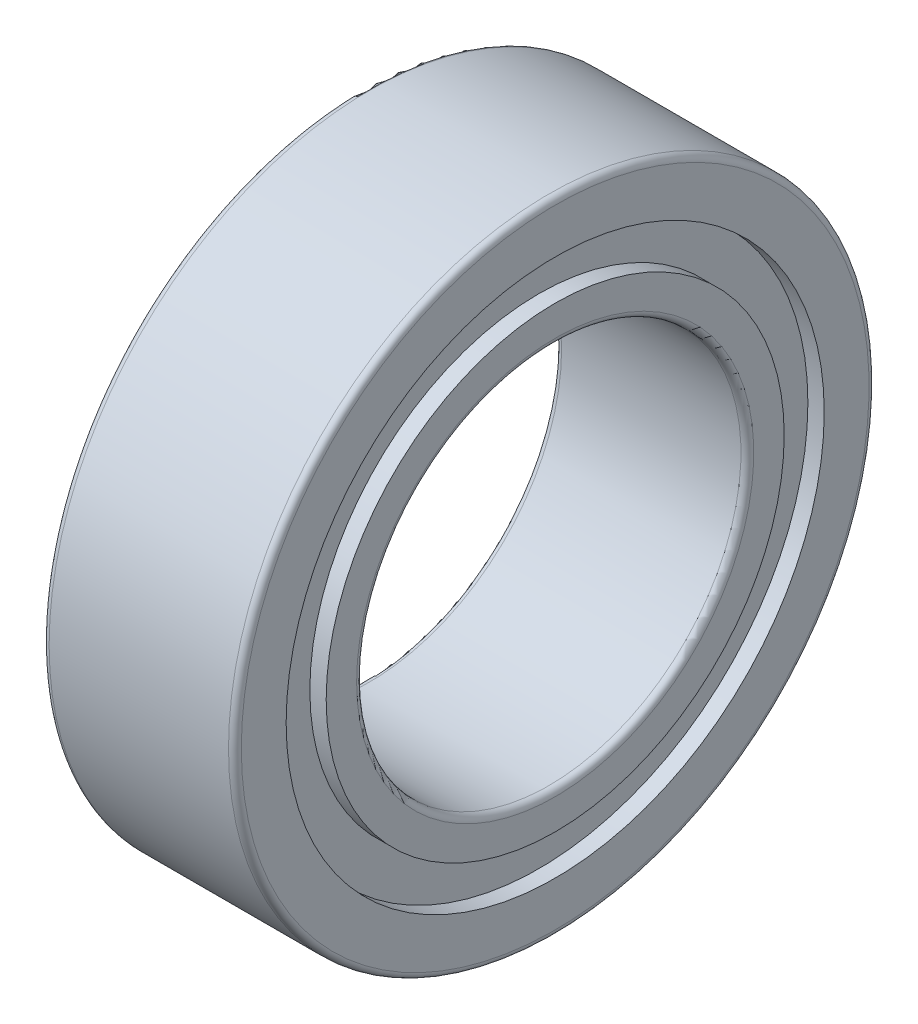
SolidWorks part; units mm, degrees
ref_plane "Front Plane" through (0, 0, 0) normal (0, 0, 1) x (1, 0, 0)
ref_plane "Top Plane" through (0, 0, 0) normal (0, 1, 0) x (1, 0, 0)
ref_plane "Right Plane" through (0, 0, 0) normal (1, 0, 0) x (0, 0, -1)
sketch "Sketch1" plane through (0, 0, 0) normal (0, 0, 1) x (1, 0, 0)
  line L0 (0, 0) -> (3, 0) construction
  line L1 (0, 3) -> (3, 3)
  line L2 (0, 5) -> (3, 5)
  line L3 (0, 5) -> (0, 4.2)
  line L4 (0, 4.2) -> (0.255, 4.2)
  line L5 (3, 5) -> (3, 4.2)
  line L6 (0.255, 4.2) -> (0.255, 3.575)
  line L7 (0.255, 3.575) -> (0, 3.575)
  line L8 (0, 3.575) -> (0, 3)
  line L9 (3, 4.2) -> (2.745, 4.2)
  line L10 (2.745, 4.2) -> (2.745, 3.575)
  line L11 (2.745, 3.575) -> (3, 3.575)
  line L12 (3, 3.575) -> (3, 3)
  dimension "D" = 10
  dimension "B" = 3
  dimension "D_s" = 6
  dimension "MSM_1" = 8.4
  dimension "MSM_2" = 7.15
  dimension "MSM_3" = 0.255
revolve "Revolve1" add sketch "Sketch1" angle 360 about L0
fillet "Fillet1" radius 0.1 2 edges at (3, 0, 5) (0, 0, 5)
fillet "Fillet2" radius 0.1 2 edges at (3, 0, 3) (0, 0, 3)
